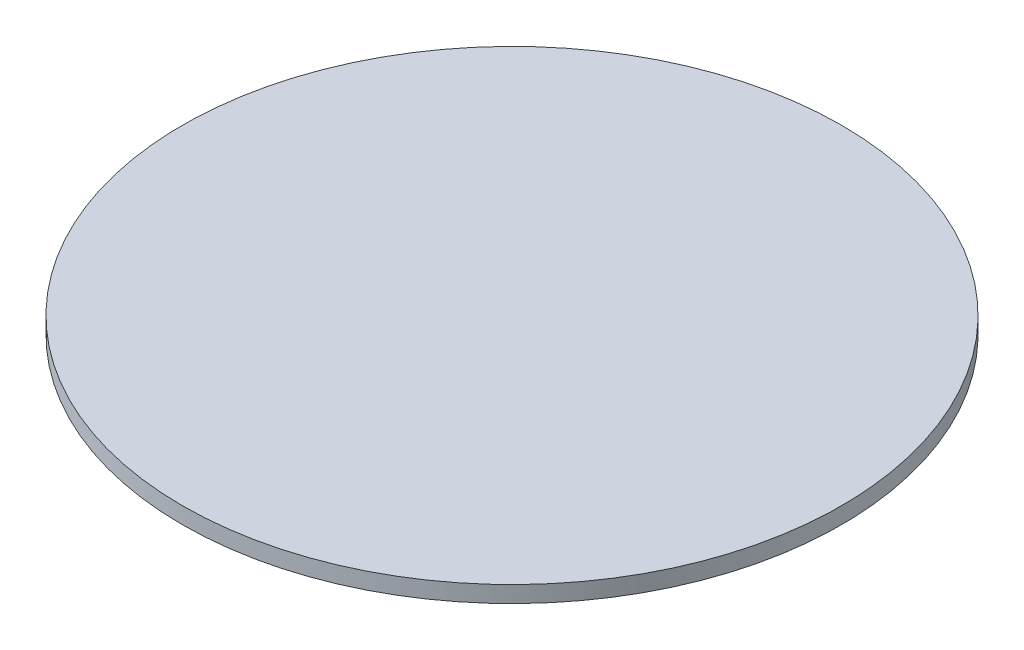
SolidWorks part; units mm, degrees
ref_plane "Front Plane" through (0, 0, 0) normal (0, 0, 1) x (1, 0, 0)
ref_plane "Top Plane" through (0, 0, 0) normal (0, 1, 0) x (1, 0, 0)
ref_plane "Right Plane" through (0, 0, 0) normal (1, 0, 0) x (0, 0, -1)
sketch "Sketch1" plane through (0, 0, 0) normal (0, 1, 0) x (1, 0, 0)
  circle A0 centre (0, 0) radius 50
  dimension "D1" = 100
extrude "Boss-Extrude1" add sketch "Sketch1" along normal blind 2.5
